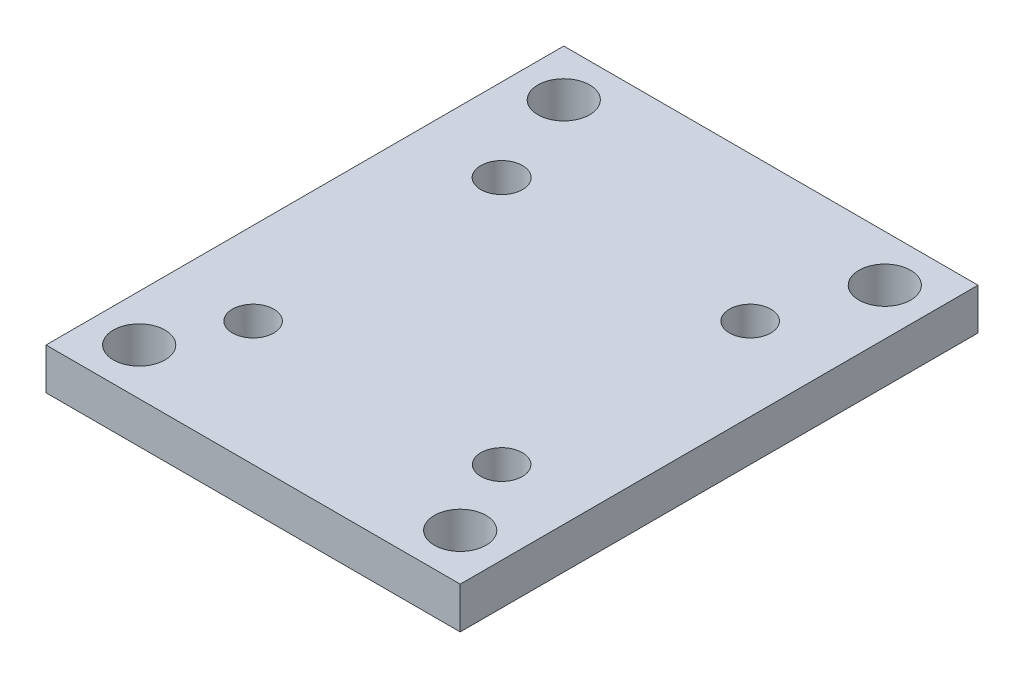
SolidWorks part; units mm, degrees
ref_plane "Front Plane" through (0, 0, 0) normal (0, 0, 1) x (1, 0, 0)
ref_plane "Top Plane" through (0, 0, 0) normal (0, 1, 0) x (1, 0, 0)
ref_plane "Right Plane" through (0, 0, 0) normal (1, 0, 0) x (0, 0, -1)
sketch "Sketch1" plane through (0, 0, 0) normal (0, 1, 0) x (1, 0, 0)
  line L1 (0, 0) -> (25.4, 0)
  line L2 (0, 0) -> (0, 31.75)
  line L3 (0, 31.75) -> (25.4, 31.75)
  line L4 (25.4, 0) -> (25.4, 31.75)
  circle A0 centre (2.8575, 28.8925) radius 1.5875
  circle A1 centre (22.5425, 28.8925) radius 1.5875
  circle A2 centre (2.8575, 2.8575) radius 1.5875
  circle A3 centre (22.5425, 2.8575) radius 1.5875
  dimension "D3" = 3.175
  dimension "D4" = 3.175
  dimension "D5" = 3.175
  dimension "D6" = 3.175
  dimension "D1" = 25.4
  dimension "D2" = 31.75
  dimension "D7" = 2.8575
  dimension "D8" = 2.8575
  dimension "D9" = 2.8575
  dimension "D10" = 2.8575
  dimension "D11" = 2.8575
  dimension "D12" = 2.8575
  dimension "D13" = 2.8575
  dimension "D14" = 2.8575
  dimension "D15" = 2.8575
extrude "Boss-Extrude1" add sketch "Sketch1" along normal blind 2.54
sketch "Sketch2" plane through (0, 2.54, 0) normal (0, 1, 0) x (1, 0, 0)
  line L0 (25.4, 31.75) -> (0, 31.75) construction
  line L1 (0, 31.75) -> (0, 0) construction
  line L2 (25.4, 0) -> (25.4, 31.75) construction
  circle A0 centre (5.08, 22.86) radius 1.2797
  circle A1 centre (20.32, 22.86) radius 1.27
  circle A2 centre (5.08, 7.62) radius 1.27
  circle A3 centre (20.32, 7.62) radius 1.27
  dimension "D1" = 2.5593
  dimension "D2" = 2.54
  dimension "D3" = 2.54
  dimension "D4" = 2.54
  dimension "D11" = 5.08
  dimension "D5" = 8.89
  dimension "D6" = 15.24
  dimension "D7" = 15.24
  dimension "D8" = 8.89
  dimension "D9" = 15.24
  dimension "D10" = 15.24
  dimension "D12" = 5.08
extrude "Cut-Extrude1" cut sketch "Sketch2" against normal through all
